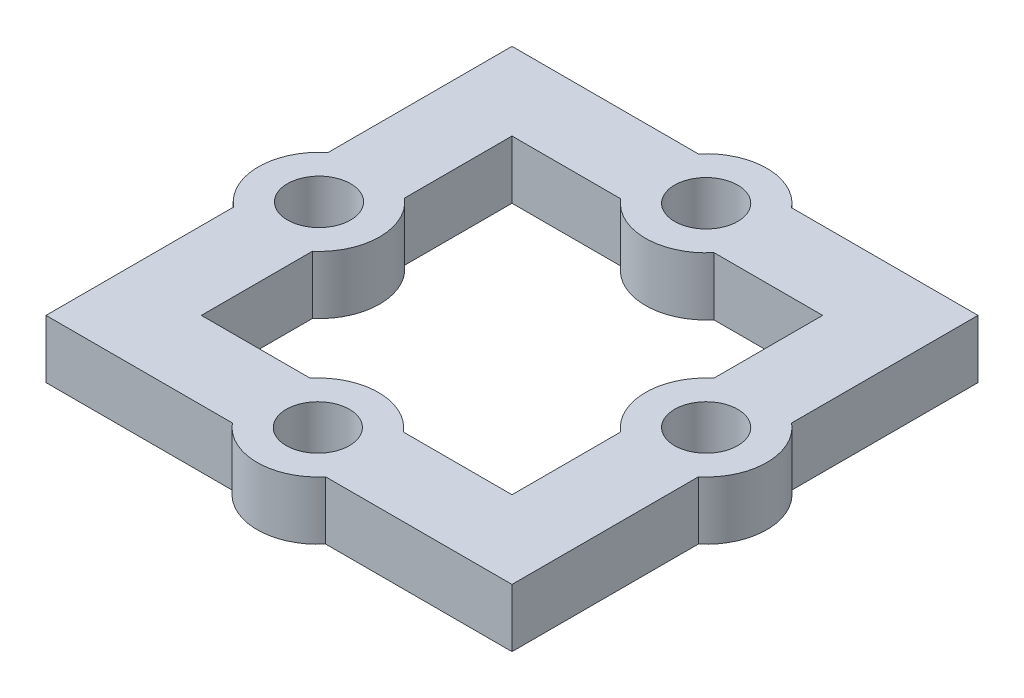
SolidWorks part; units mm, degrees
ref_plane "Спереди" through (0, 0, 0) normal (0, 0, 1) x (1, 0, 0)
ref_plane "Сверху" through (0, 0, 0) normal (0, 1, 0) x (1, 0, 0)
ref_plane "Справа" through (0, 0, 0) normal (1, 0, 0) x (0, 0, -1)
sketch "Sketch1" plane through (0, 0, 0) normal (0, 1, 0) x (1, 0, 0)
  line L0 (-24, -4.6689) -> (-24, -24)
  line L1 (-24, 24) -> (-4.8023, 24)
  line L2 (-24, 24) -> (-24, 5.0436)
  line L3 (-24, -24) -> (-4.8023, -24)
  line L4 (24, 24) -> (24, 4.8023)
  line L5 (-24, 24) -> (24, -24) construction
  line L6 (-24, -24) -> (24, 24) construction
  line L7 (-16, 16) -> (-4.8023, 16)
  line L8 (-16, 16) -> (-16, 4.9342)
  line L9 (-16, -16) -> (-4.8023, -16)
  line L10 (16, 16) -> (16, 4.8023)
  line L11 (-16, 16) -> (16, -16) construction
  line L12 (-16, -16) -> (16, 16) construction
  line L13 (-16, -4.5595) -> (-16, -16)
  line L14 (4.8023, 16) -> (16, 16)
  line L15 (4.8023, 24) -> (24, 24)
  line L16 (16, -4.8023) -> (16, -16)
  line L17 (4.8023, -16) -> (16, -16)
  line L18 (4.8023, -24) -> (24, -24)
  line L19 (24, -4.8023) -> (24, -24)
  circle A0 centre (-20.0657, 0.1873) radius 3.25
  circle A1 centre (0, 20) radius 3.25
  circle A2 centre (20, 0) radius 3.25
  circle A3 centre (0, -20) radius 3.25
  arc A4 (12, -16) -> (6.1732, -19.0234) centre (0, 0) ccw construction
  arc A5 (-24, 5.0436) -> (-24, -4.6689) centre (-20.0657, 0.1873) ccw
  arc A6 (-4.8023, 16) -> (4.8023, 16) centre (0, 20) ccw
  arc A7 (16, 4.8023) -> (16, -4.8023) centre (20, 0) ccw
  arc A8 (4.8023, -16) -> (-4.8023, -16) centre (0, -20) ccw
  arc A9 (-16, -4.5595) -> (-16, 4.9342) centre (-20.0657, 0.1873) ccw
  arc A10 (4.8023, 24) -> (-4.8023, 24) centre (0, 20) ccw
  arc A11 (24, -4.8023) -> (24, 4.8023) centre (20, 0) ccw
  arc A12 (-4.8023, -24) -> (4.8023, -24) centre (0, -20) ccw
  point P0 (0, 0)
  point P6 (0, 0)
  dimension "D3" = 40
  dimension "D4" = 6.5
  dimension "D5" = 12.5
  dimension "D6" = 6.5
  dimension "D7" = 12.5
  dimension "D8" = 6.5
  dimension "D9" = 12.5
  dimension "D10" = 6.5
  dimension "D11" = 12.5
  dimension "D1" = 48
  dimension "D2" = 32
  dimension "D12" = 32
extrude "Boss-Extrude1" add sketch "Sketch1" along normal blind 6 contours L4 A11 L19 L18 A12 L3 L0 A5 L2 L1 A10 L15 | A8 L9 L13 A9 L8 L7 A6 L14 L10 A7 L16 L17 | A1 | A3 | A2 | A0
